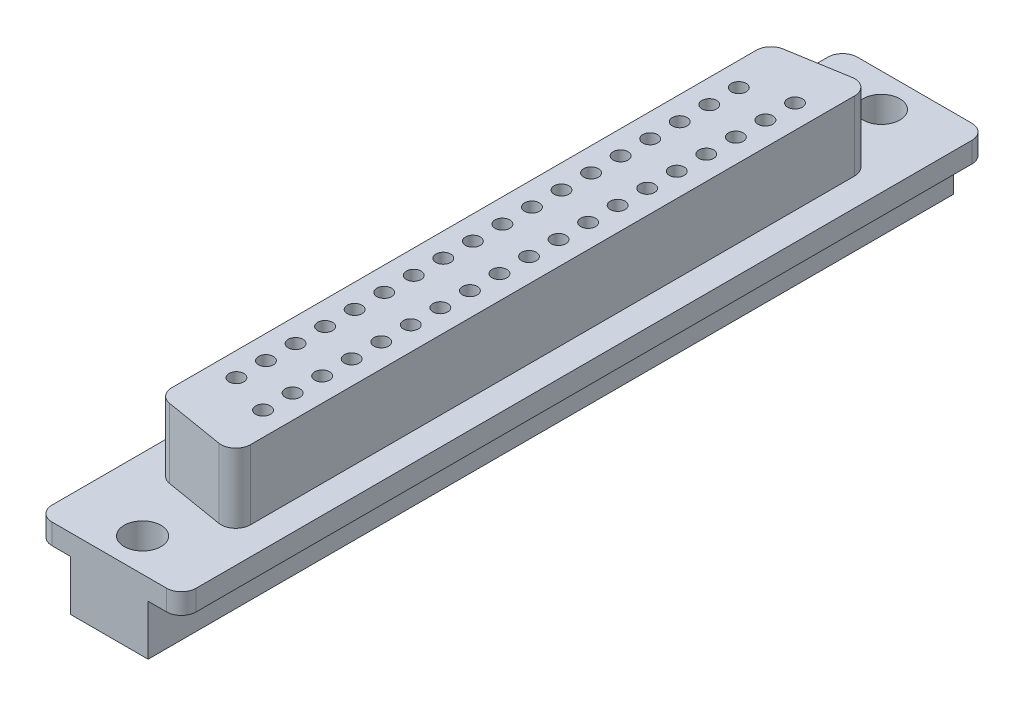
SolidWorks part; units mm, degrees
ref_plane "Front Plane" through (0, 0, 0) normal (0, 0, 1) x (1, 0, 0)
ref_plane "Top Plane" through (0, 0, 0) normal (0, 1, 0) x (1, 0, 0)
ref_plane "Right Plane" through (0, 0, 0) normal (1, 0, 0) x (0, 0, -1)
sketch "Sketch1" plane through (0, 0, 0) normal (0, 1, 0) x (1, 0, 0)
  line L1 (0, 0) -> (6.6675, 0)
  line L2 (0, 0) -> (0, 69.215)
  line L3 (0, 69.215) -> (6.6675, 69.215)
  line L4 (6.6675, 0) -> (6.6675, 69.215)
  dimension "D1" = 69.215
  dimension "D2" = 6.6675
extrude "Extrude1" add sketch "Sketch1" along normal blind 4.318
sketch "Sketch2" plane through (0, 4.318, 0) normal (0, 1, 0) x (1, 0, 0)
  line L1 (-1.5875, 69.215) -> (8.255, 69.215)
  line L2 (-2.8575, 67.945) -> (-2.8575, 1.27)
  line L3 (-1.5875, 0) -> (8.255, 0)
  line L4 (9.525, 67.945) -> (9.525, 1.27)
  line L5 (0, 69.215) -> (0, 0) construction
  arc A0 (-1.5875, 69.215) -> (-2.8575, 67.945) centre (-1.5875, 67.945) ccw
  arc A1 (8.255, 69.215) -> (9.525, 67.945) centre (8.255, 67.945) cw
  arc A2 (8.255, 0) -> (9.525, 1.27) centre (8.255, 1.27) ccw
  arc A3 (-2.8575, 1.27) -> (-1.5875, 0) centre (-1.5875, 1.27) ccw
  point P8 (-2.8575, 69.215)
  point P11 (9.525, 69.215)
  dimension "D4" = 1.27
  dimension "D1" = 69.215
  dimension "D2" = 2.8575
  dimension "D3" = 12.3825
extrude "Extrude2" add sketch "Sketch2" along normal blind 1.7653
sketch "Sketch3" plane through (0, 6.0833, 0) normal (0, 1, 0) x (1, 0, 0)
  line L0 (-0.4763, 59.4079) -> (-0.4762, 9.1721)
  line L1 (0.585, 7.9194) -> (5.665, 7.0727)
  line L2 (7.1438, 8.3254) -> (7.1438, 60.2546)
  line L3 (5.665, 61.5073) -> (0.585, 60.6606)
  line L5 (-2.8575, 67.945) -> (-2.8575, 1.27) construction
  line L6 (8.255, 69.215) -> (-1.5875, 69.215) construction
  arc A0 (-0.4763, 59.4079) -> (0.585, 60.6606) centre (0.7938, 59.4079) cw
  arc A1 (7.1438, 60.2546) -> (5.665, 61.5073) centre (5.8738, 60.2546) ccw
  arc A2 (5.665, 7.0727) -> (7.1438, 8.3254) centre (5.8738, 8.3254) ccw
  arc A3 (-0.4762, 9.1721) -> (0.585, 7.9194) centre (0.7938, 9.1721) ccw
  point P11 (-0.4763, 60.4837)
  point P14 (7.1438, 61.7537)
  point P17 (7.1438, 6.8262)
  point P20 (-0.4762, 8.0962)
  dimension "D7" = 1.27
  dimension "D1" = 54.9275
  dimension "D2" = 52.3875
  dimension "D3" = 7.62
  dimension "D4" = 2.3813
  dimension "D5" = 7.4612
  dimension "D6" = 1.27
extrude "Extrude3" add sketch "Sketch3" along normal blind 5.969
sketch "Sketch4" plane through (0, 6.0833, 0) normal (0, 1, 0) x (1, 0, 0)
  line L0 (-1.5875, 0) -> (8.255, 0) construction
  line L1 (8.255, 69.215) -> (-1.5875, 69.215) construction
  line L2 (-2.8575, 67.945) -> (-2.8575, 1.27) construction
  circle A0 centre (3.3337, 66.3575) radius 1.5875
  circle A1 centre (3.3337, 2.8575) radius 1.5875
  dimension "D1" = 3.175
  dimension "D2" = 3.175
  dimension "D3" = 2.8575
  dimension "D4" = 2.8575
  dimension "D5" = 6.1913
  dimension "D6" = 6.1913
extrude "Extrude4" cut sketch "Sketch4" against normal through all
sketch "Sketch5" plane through (0, 12.0523, 0) normal (0, 1, 0) x (1, 0, 0)
  line L0 (7.1438, 8.3254) -> (7.1438, 60.2546) construction
  line L1 (-0.4763, 59.4079) -> (-0.4762, 9.1721) construction
  line L3 (-0.4762, 34.29) -> (17.9079, 34.29) construction
  circle A0 centre (5.1118, 57.15) radius 0.635
  circle A1 centre (1.5557, 55.88) radius 0.635
  circle A2 centre (5.1118, 54.61) radius 0.635
  circle A3 centre (5.1118, 52.07) radius 0.635
  circle A4 centre (5.1118, 49.53) radius 0.635
  circle A5 centre (5.1118, 46.99) radius 0.635
  circle A6 centre (5.1118, 44.45) radius 0.635
  circle A7 centre (5.1118, 41.91) radius 0.635
  circle A8 centre (5.1118, 39.37) radius 0.635
  circle A9 centre (5.1118, 36.83) radius 0.635
  circle A10 centre (5.1118, 34.29) radius 0.635
  circle A11 centre (5.1118, 31.75) radius 0.635
  circle A12 centre (5.1118, 29.21) radius 0.635
  circle A13 centre (5.1118, 26.67) radius 0.635
  circle A14 centre (5.1118, 24.13) radius 0.635
  circle A15 centre (5.1118, 21.59) radius 0.635
  circle A16 centre (5.1118, 19.05) radius 0.635
  circle A17 centre (5.1118, 16.51) radius 0.635
  circle A18 centre (5.1118, 13.97) radius 0.635
  circle A19 centre (5.1118, 11.43) radius 0.635
  circle A20 centre (5.1118, 54.61) radius 0.635
  circle A21 centre (1.5558, 53.34) radius 0.635
  circle A22 centre (5.1118, 52.07) radius 0.635
  circle A23 centre (1.5558, 50.8) radius 0.635
  circle A24 centre (5.1118, 49.53) radius 0.635
  circle A25 centre (1.5558, 48.26) radius 0.635
  circle A26 centre (5.1118, 46.99) radius 0.635
  circle A27 centre (1.5558, 45.72) radius 0.635
  circle A28 centre (5.1118, 44.45) radius 0.635
  circle A29 centre (1.5558, 43.18) radius 0.635
  circle A30 centre (5.1118, 41.91) radius 0.635
  circle A31 centre (1.5558, 40.64) radius 0.635
  circle A32 centre (5.1118, 39.37) radius 0.635
  circle A33 centre (1.5558, 38.1) radius 0.635
  circle A34 centre (5.1118, 36.83) radius 0.635
  circle A35 centre (1.5558, 35.56) radius 0.635
  circle A36 centre (5.1118, 34.29) radius 0.635
  circle A37 centre (1.5558, 33.02) radius 0.635
  circle A38 centre (5.1118, 31.75) radius 0.635
  circle A39 centre (1.5558, 30.48) radius 0.635
  circle A40 centre (5.1118, 29.21) radius 0.635
  circle A41 centre (1.5558, 27.94) radius 0.635
  circle A42 centre (5.1118, 26.67) radius 0.635
  circle A43 centre (1.5558, 25.4) radius 0.635
  circle A44 centre (5.1118, 24.13) radius 0.635
  circle A45 centre (1.5558, 22.86) radius 0.635
  circle A46 centre (5.1118, 21.59) radius 0.635
  circle A47 centre (1.5558, 20.32) radius 0.635
  circle A48 centre (5.1118, 19.05) radius 0.635
  circle A49 centre (1.5558, 17.78) radius 0.635
  circle A50 centre (5.1118, 16.51) radius 0.635
  circle A51 centre (1.5558, 15.24) radius 0.635
  circle A52 centre (5.1118, 13.97) radius 0.635
  circle A53 centre (1.5558, 12.7) radius 0.635
  dimension "D1" = 1.27
  dimension "D4" = 1.27
  dimension "D2" = 2.032
  dimension "D3" = 2.032
extrude "Extrude5" cut sketch "Sketch5" against normal blind 6.35 contours A5 | A4 | A3 | A2 | A0 | A1 | A21 | A23 | A7 | A6 | A27 | A29 | A31 | A33 | A35 | A37 | A39 | A41 | A43 | A45 | A47 | A49 | A51 | A53 | A19 | A18 | A17 | A16 | A15 | A14 | A13 | A12 | A11 | A10 | A9 | A8 | A25
